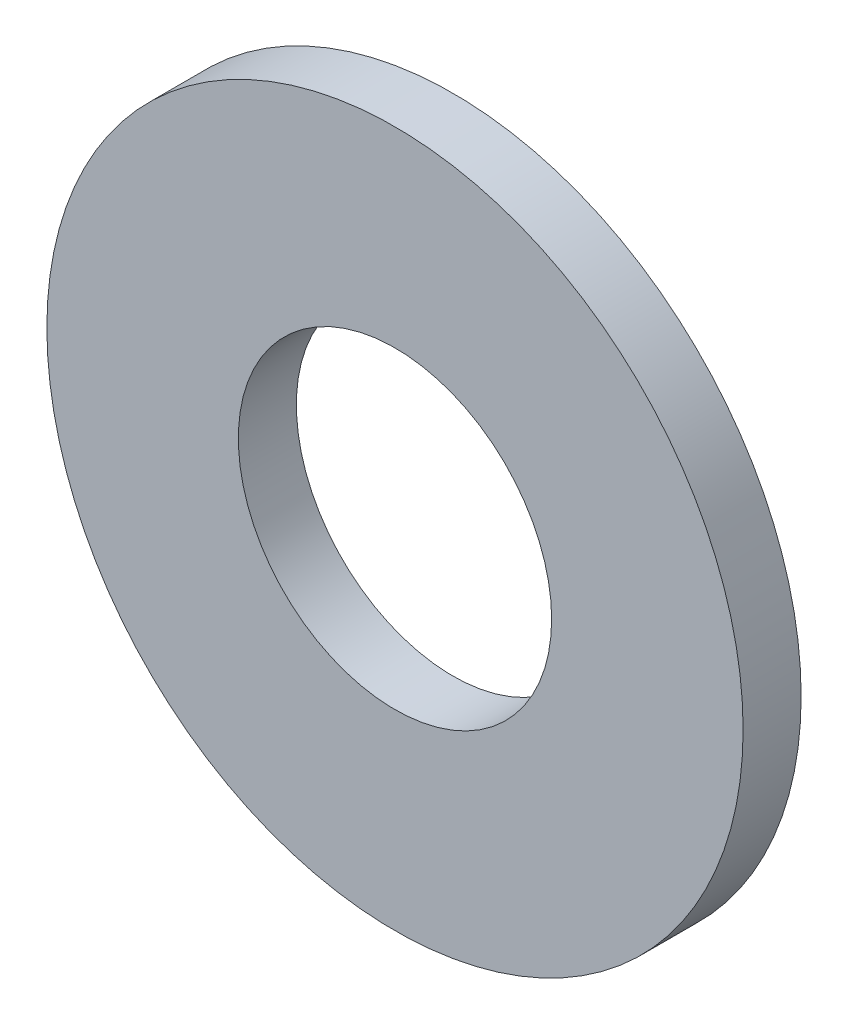
SolidWorks part; units mm, degrees
ref_plane "Спереди" through (0, 0, 0) normal (0, 0, 1) x (1, 0, 0)
ref_plane "Сверху" through (0, 0, 0) normal (0, 1, 0) x (1, 0, 0)
ref_plane "Справа" through (0, 0, 0) normal (1, 0, 0) x (0, 0, -1)
sketch "Эскиз1" plane through (0, 0, 0) normal (0, 0, 1) x (1, 0, 0)
  circle A0 centre (0, 0) radius 3
  circle A1 centre (0, 0) radius 1.35
  dimension "D1" = 6
  dimension "D2" = 2.7
extrude "Вытянуть1" add sketch "Эскиз1" along normal blind 0.5
